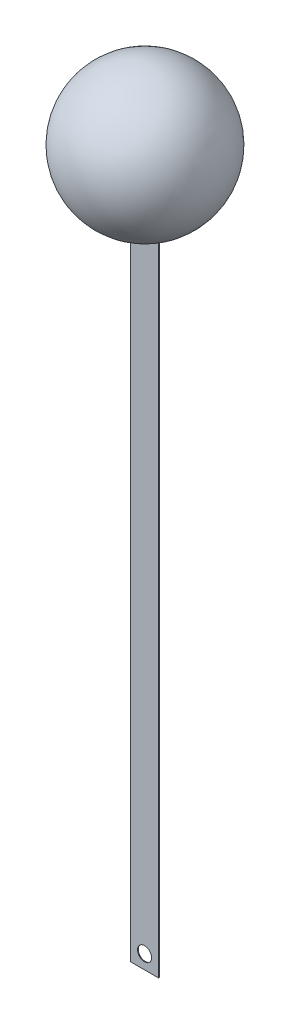
SolidWorks part; units mm, degrees
ref_plane "Front Plane" through (0, 0, 0) normal (0, 0, 1) x (1, 0, 0)
ref_plane "Top Plane" through (0, 0, 0) normal (0, 1, 0) x (1, 0, 0)
ref_plane "Right Plane" through (0, 0, 0) normal (1, 0, 0) x (0, 0, -1)
sketch "Sketch1" plane through (0, 0, 0) normal (0, 0, 1) x (1, 0, 0)
  line L0 (0, 510) -> (0, 0) construction
  line L1 (-10, 0) -> (10, 0)
  line L4 (-10, 510) -> (10, 510)
  line L5 (0, 460) -> (0, 560)
  circle A0 centre (0, 510) radius 50
  point P4 (0, 0)
  dimension "D1" = 100
  dimension "D2" = 510
  dimension "D3" = 20
revolve "Revolve3" add sketch "Sketch1" angle 360 about L0
sketch "Sketch6" plane through (0, 0, 0) normal (0, 1, 0) x (1, 0, 0)
  line L1 (-10, -0.25) -> (10, -0.25)
  line L2 (-10, -0.25) -> (-10, 0.25)
  line L3 (-10, 0.25) -> (10, 0.25)
  line L4 (10, -0.25) -> (10, 0.25)
  line L5 (-10, -0.25) -> (10, 0.25) construction
  line L6 (-10, 0.25) -> (10, -0.25) construction
  point P0 (0, 0)
  dimension "D1" = 20
  dimension "D2" = 0.5
extrude "Boss-Extrude2" add sketch "Sketch6" along normal up to surface (461.0108 mm away)
sketch "Sketch7" plane through (0, 0, 0.25) normal (0, 0, 1) x (1, 0, 0)
  line L0 (-10, 0) -> (10, 0) construction
  circle A0 centre (0, 10) radius 5
  dimension "D2" = 10
  dimension "D1" = 10
extrude "Cut-Extrude1" cut sketch "Sketch7" against normal through all both and the other way through all
